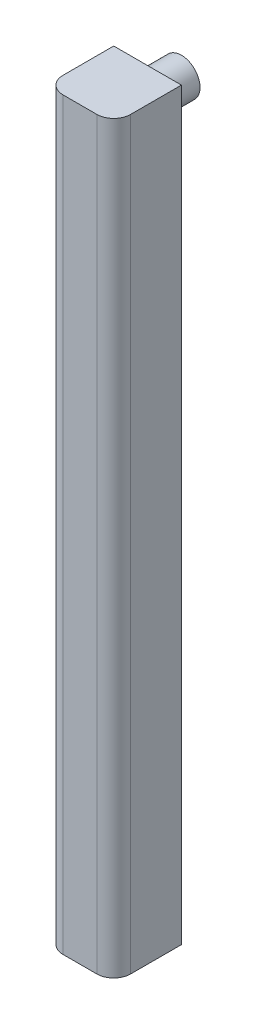
SolidWorks part; units mm, degrees
ref_plane "Front Plane" through (0, 0, 0) normal (0, 0, 1) x (1, 0, 0)
ref_plane "Top Plane" through (0, 0, 0) normal (0, 1, 0) x (1, 0, 0)
ref_plane "Right Plane" through (0, 0, 0) normal (1, 0, 0) x (0, 0, -1)
sketch "Sketch2" plane through (0, 0, 0) normal (0, 0, 1) x (1, 0, 0)
  line L0 (0, 0) -> (0, 110)
  line L1 (0, 110) -> (10, 110)
  line L2 (10, 110) -> (10, 0)
  line L3 (10, 0) -> (0, 0)
extrude "Boss-Extrude1" add sketch "Sketch2" along normal blind 10
sketch "Sketch3" plane through (0, 0, 0) normal (0, 0, -1) x (-1, 0, 0)
  circle A1 centre (-5, 106.0744) radius 2.75
extrude "Boss-Extrude2" add sketch "Sketch3" along normal blind 5
fillet "Fillet2" radius 2.5 2 edges at (0, 55, 10) (10, 55, 10)
